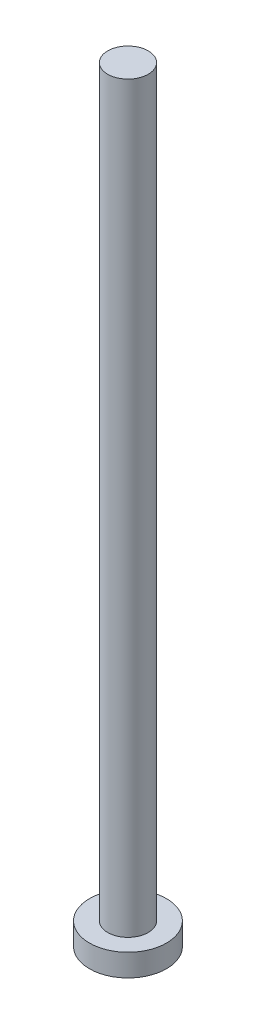
SolidWorks part; units mm, degrees
ref_plane "前视基准面" through (0, 0, 0) normal (0, 0, 1) x (1, 0, 0)
ref_plane "上视基准面" through (0, 0, 0) normal (0, 1, 0) x (1, 0, 0)
ref_plane "右视基准面" through (0, 0, 0) normal (1, 0, 0) x (0, 0, -1)
sketch "草图1" plane through (0, 0, 0) normal (0, 1, 0) x (1, 0, 0)
  circle A0 centre (0, 0) radius 2.85
  dimension "D1" = 5.7
extrude "凸台-拉伸1" add sketch "草图1" along normal blind 1.65
sketch "草图2" plane through (0, 1.65, 0) normal (0, 1, 0) x (1, 0, 0)
  circle A0 centre (0, 0) radius 1.5
  dimension "D1" = 3
extrude "凸台-拉伸2" add sketch "草图2" along normal blind 55
